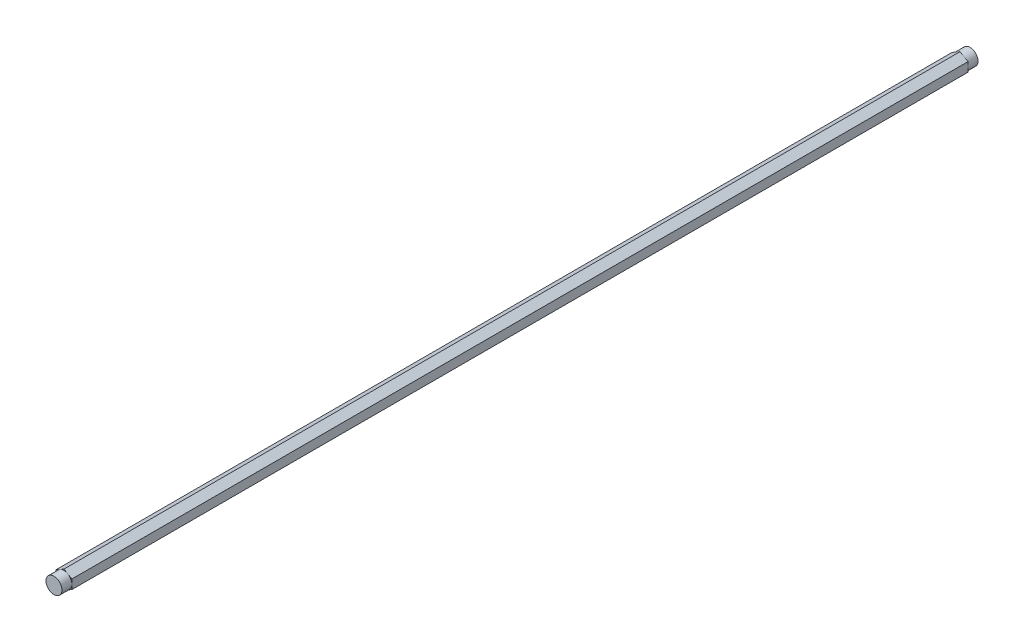
SolidWorks part; units mm, degrees
ref_plane "Front Plane" through (0, 0, 0) normal (0, 0, 1) x (1, 0, 0)
ref_plane "Top Plane" through (0, 0, 0) normal (0, 1, 0) x (1, 0, 0)
ref_plane "Right Plane" through (0, 0, 0) normal (1, 0, 0) x (0, 0, -1)
sketch "Sketch1" plane through (0, 0, 0) normal (0, 0, 1) x (1, 0, 0)
  line L1 (6.35, 3.6662) -> (0, 7.3323)
  line L2 (0, 7.3323) -> (-6.35, 3.6662)
  line L3 (-6.35, 3.6662) -> (-6.35, -3.6662)
  line L4 (-6.35, -3.6662) -> (0, -7.3323)
  line L5 (0, -7.3323) -> (6.35, -3.6662)
  line L6 (6.35, -3.6662) -> (6.35, 3.6662)
  circle A0 centre (0, 0) radius 6.35 construction
  dimension "D1" = 12.7
extrude "Boss-Extrude1" add sketch "Sketch1" along normal mid plane 730.0722
sketch "Sketch2" plane through (0, 0, 365.0361) normal (0, 0, 1) x (1, 0, 0)
  circle A0 centre (0, 0) radius 6.35
  dimension "D1" = 12.7
extrude "Cut-Extrude1" cut sketch "Sketch2" against normal blind 7.9502 flip side to cut
mirror "Mirror1" about plane through (0, 0, 0) normal (0, 0, 1) of "Cut-Extrude1"
